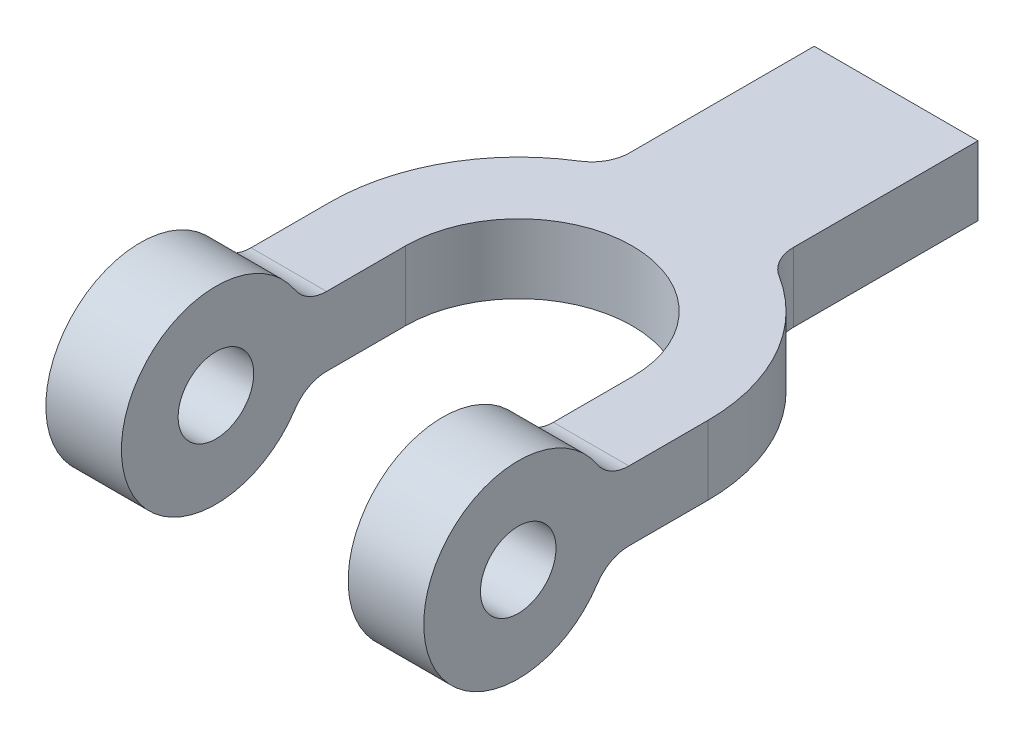
SolidWorks part; units mm, degrees
ref_plane "Front Plane" through (0, 0, 0) normal (0, 0, 1) x (1, 0, 0)
ref_plane "Top Plane" through (0, 0, 0) normal (0, 1, 0) x (1, 0, 0)
ref_plane "Right Plane" through (0, 0, 0) normal (1, 0, 0) x (0, 0, -1)
sketch "Sketch2" plane through (0, 0, 0) normal (0, 1, 0) x (1, 0, 0)
  line L1 (100, -175) -> (-100, -175)
  line L2 (100, -175) -> (100, 175)
  line L3 (100, 175) -> (-100, 175)
  line L4 (-100, -175) -> (-100, 175)
  line L5 (100, -175) -> (-100, 175) construction
  line L6 (100, 175) -> (-100, -175) construction
  point P0 (0, 0)
  dimension "D1" = 200
  dimension "D2" = 350
extrude "Boss-Extrude1" add sketch "Sketch2" along normal blind 100
sketch "Sketch3" plane through (0, 100, 0) normal (0, 1, 0) x (1, 0, 0)
  line L0 (0, 0) -> (0, -175) construction
  line L1 (-100, -175) -> (100, -175) construction
  line L2 (0, -175) -> (0, 175) construction
  line L3 (100, 175) -> (-100, 175) construction
  line L4 (-43.3476, 175) -> (-43.3476, 77.2727)
  line L5 (43.3476, 175) -> (43.3476, 77.2727)
  circle A0 centre (0, -24.6443) radius 60
  arc A1 (-52.7897, 60.2865) -> (52.7897, 60.2865) centre (0, -24.6443) ccw
  arc A2 (-43.3476, 77.2727) -> (-52.7897, 60.2865) centre (-63.3476, 77.2727) cw
  arc A3 (52.7897, 60.2865) -> (43.3476, 77.2727) centre (63.3476, 77.2727) cw
  point P16 (-43.3476, 65.4722)
  point P19 (43.3476, 65.4722)
  dimension "D1" = 120
  dimension "D2" = 20
  dimension "D3" = 20
sketch "Sketch4" plane through (0, 100, 0) normal (0, 1, 0) x (1, 0, 0)
  line L0 (43.3476, 175) -> (43.3476, 77.2727) construction
  line L1 (-43.3476, 175) -> (-43.3476, 77.2727) construction
  line L2 (43.3476, 175) -> (43.3476, 77.2727)
  line L3 (-43.3476, 175) -> (-43.3476, 77.2727)
  line L4 (-60, -24.6443) -> (-60, -175)
  line L5 (-100, -175) -> (100, -175) construction
  line L6 (0, -24.6443) -> (0, -175) construction
  line L7 (60, -24.6443) -> (60, -175)
  line L8 (-100, 175) -> (-100, -175) construction
  line L9 (100, -175) -> (100, 175) construction
  line L10 (-100, 175) -> (-100, -175)
  line L11 (100, -175) -> (100, 175)
  line L12 (100, 175) -> (-100, 175) construction
  line L13 (100, 175) -> (-100, 175)
  line L14 (-100, -175) -> (100, -175)
  arc A0 (43.3476, 77.2727) -> (52.7897, 60.2865) centre (63.3476, 77.2727) ccw construction
  circle A1 centre (0, -24.6443) radius 60
  circle A2 centre (0, -24.6443) radius 60
  arc A3 (-52.7897, 60.2865) -> (52.7897, 60.2865) centre (0, -24.6443) ccw construction
  arc A4 (-52.7897, 60.2865) -> (-43.3476, 77.2727) centre (-63.3476, 77.2727) ccw construction
  arc A5 (43.3476, 77.2727) -> (52.7897, 60.2865) centre (63.3476, 77.2727) ccw
  arc A6 (-52.7897, 60.2865) -> (52.7897, 60.2865) centre (0, -24.6443) ccw
  arc A7 (-52.7897, 60.2865) -> (-43.3476, 77.2727) centre (-63.3476, 77.2727) ccw
  dimension "D1" = 0
extrude "Cut-Extrude3" cut sketch "Sketch4" against normal through all
sketch "Sketch5" plane through (100, 0, 0) normal (1, 0, 0) x (0, 0, -1)
  line L0 (-175, 100) -> (-175, 0) construction
  line L1 (-175, 50) -> (175, 50) construction
  line L2 (175, 0) -> (175, 100) construction
  line L3 (-66.42, 68.3195) -> (175, 68.3195)
  line L4 (-66.42, 31.6805) -> (175, 31.6805)
  line L5 (-175, 0) -> (-24.6443, 0) construction
  line L6 (77.2727, 100) -> (60.2865, 100) construction
  line L7 (60.2865, 100) -> (-124.6443, 100) construction
  line L8 (-24.6443, 0) -> (60.2865, 0) construction
  line L9 (175, 100) -> (77.2727, 100)
  line L10 (77.2727, 100) -> (77.2727, 0)
  line L11 (77.2727, 0) -> (175, 0)
  line L12 (175, 0) -> (175, 100)
  line L13 (175, 100) -> (77.2727, 100)
  line L14 (77.2727, 100) -> (77.2727, 0)
  line L15 (77.2727, 0) -> (175, 0)
  line L16 (175, 0) -> (175, 100)
  line L17 (60.2865, 0) -> (77.2727, 0) construction
  line L18 (-175, 0) -> (-24.6443, 0)
  line L19 (77.2727, 100) -> (60.2865, 100)
  line L20 (60.2865, 100) -> (-124.6443, 100)
  line L21 (-24.6443, 0) -> (60.2865, 0)
  line L22 (60.2865, 0) -> (77.2727, 0)
  arc A0 (-83.1572, 77.3711) -> (-83.1572, 22.6289) centre (-125, 50) ccw
  circle A1 centre (-125, 50) radius 20
  arc A2 (-66.42, 68.3195) -> (-83.1572, 77.3711) centre (-66.42, 88.3195) cw
  arc A3 (-66.42, 31.6805) -> (-83.1572, 22.6289) centre (-66.42, 11.6805) ccw
  point P5 (-175, 50)
  point P15 (-78.4769, 68.3195)
  point P18 (-78.4769, 31.6805)
  line M1 (-175, 0) -> (-24.6443, 0)
  line M2 (-24.6443, 0) -> (-24.6443, 100)
  line M3 (-24.6443, 100) -> (-175, 100)
  line M4 (-175, 100) -> (-175, 0)
  dimension "D1" = 100
  dimension "D2" = 40
  dimension "D3" = 20
  dimension "D4" = 20
  dimension "D5" = 0
extrude "Cut-Extrude4" cut sketch "Sketch5" against normal through all contours A0 M3 M4 | A1 L1 | L1 A1 | A0 M4 M1 | L4 A3 A0 L18 M2 | A2 L3 A0 M2 M3 | L19 L20 L3 L14 M2 | L21 L22 L14 L4 M2 | L15 L16 L4 L14 | L3 L16 L13 L14
scale "Scale1" scale about centroid uniform scaling yes scale factor 0.35
